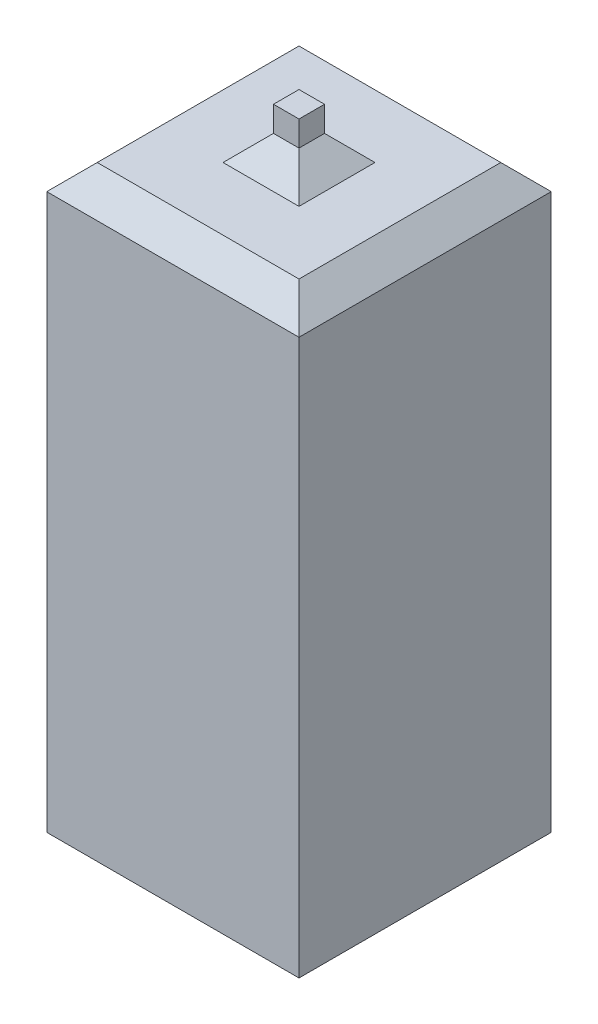
SolidWorks part; units mm, degrees
ref_plane "Front Plane" through (0, 0, 0) normal (0, 0, 1) x (1, 0, 0)
ref_plane "Top Plane" through (0, 0, 0) normal (0, 1, 0) x (1, 0, 0)
ref_plane "Right Plane" through (0, 0, 0) normal (1, 0, 0) x (0, 0, -1)
sketch "Sketch1" plane through (0, 0, 0) normal (0, 1, 0) x (1, 0, 0)
  line L1 (-250, 250) -> (250, 250)
  line L2 (-250, 250) -> (-250, -250)
  line L3 (-250, -250) -> (250, -250)
  line L4 (250, 250) -> (250, -250)
  line L5 (-250, 250) -> (250, -250) construction
  line L6 (-250, -250) -> (250, 250) construction
  point P0 (0, 0)
extrude "Boss-Extrude1" add sketch "Sketch1" along normal blind 1200
sketch "Sketch2" plane through (0, 1200, 0) normal (0, 1, 0) x (1, 0, 0)
  line L1 (-25.2984, 25.2984) -> (25.2984, 25.2984)
  line L2 (-25.2984, 25.2984) -> (-25.2984, -25.2984)
  line L3 (-25.2984, -25.2984) -> (25.2984, -25.2984)
  line L4 (25.2984, 25.2984) -> (25.2984, -25.2984)
  line L5 (-25.2984, 25.2984) -> (25.2984, -25.2984) construction
  line L6 (-25.2984, -25.2984) -> (25.2984, 25.2984) construction
  point P0 (0, 0)
extrude "Boss-Extrude2" add sketch "Sketch2" along normal blind 100
chamfer "Chamfer1" distance 50 angle 45 12 edges at (0, 0, -250) (-250, 0, 0) (0, 0, 250) (250, 0, 0) (0, 1200, 250) (-250, 1200, 0) (0, 1200, -250) (250, 1200, 0) (0, 1200, -25.2984) (-25.2984, 1200, 0) (0, 1200, 25.2984) (25.2984, 1200, 0)
